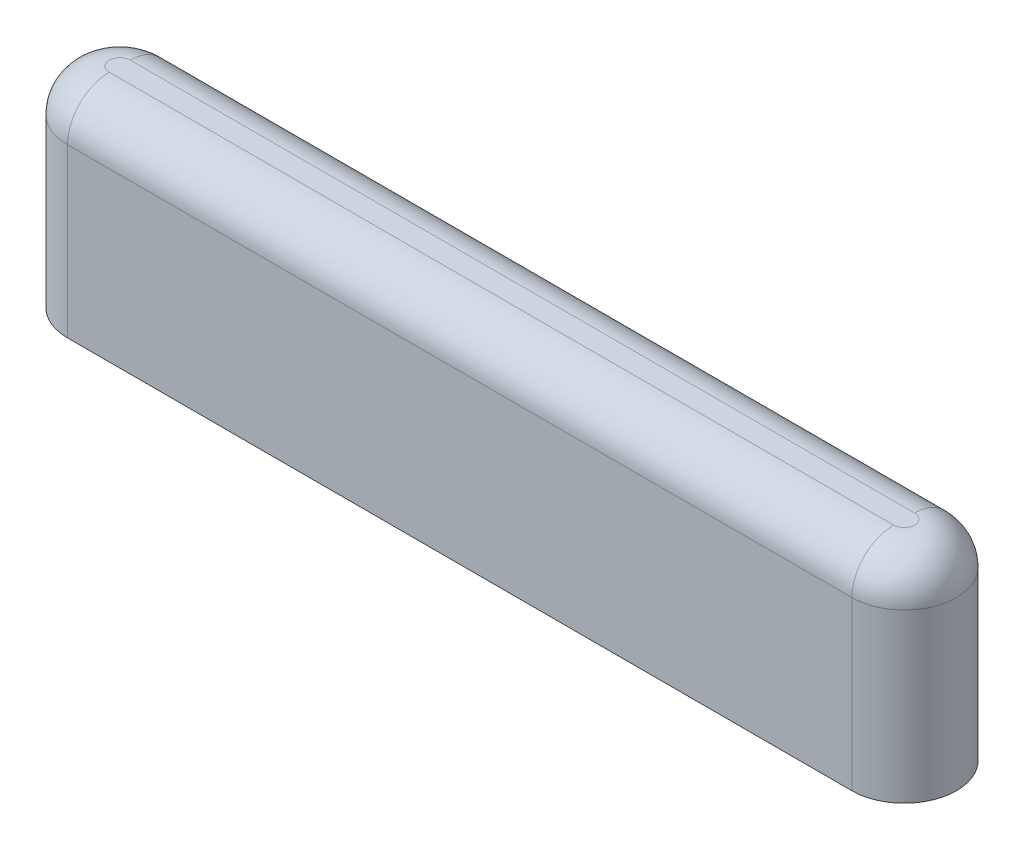
SolidWorks part; units mm, degrees
material "1060 Alloy"
ref_plane "Front Plane" through (0, 0, 0) normal (0, 0, 1) x (1, 0, 0)
ref_plane "Top Plane" through (0, 0, 0) normal (0, 1, 0) x (1, 0, 0)
ref_plane "Right Plane" through (0, 0, 0) normal (1, 0, 0) x (0, 0, -1)
sketch "Sketch1" plane through (0, 0, 0) normal (0, 1, 0) x (1, 0, 0)
  line L1 (37.5, -5) -> (-37.5, -5)
  line L2 (37.5, -5) -> (37.5, 5) construction
  line L3 (37.5, 5) -> (-37.5, 5)
  line L4 (-37.5, -5) -> (-37.5, 5) construction
  line L5 (37.5, -5) -> (-37.5, 5) construction
  line L6 (37.5, 5) -> (-37.5, -5) construction
  arc A0 (-37.5, -5) -> (-37.5, 5) centre (-37.5, 0) cw
  arc A1 (37.5, -5) -> (37.5, 5) centre (37.5, 0) ccw
  point P0 (0, 0)
  dimension "D1" = 75
  dimension "D2" = 10
extrude "Boss-Extrude1" add sketch "Sketch1" along normal blind 20 contours L1 A0 L3 A1
fillet "Fillet1" radius 4 4 edges at (42.5, 20, 0) (0, 20, -5) (-42.5, 20, 0) (0, 20, 5)
sketch "Sketch2" plane through (0, 0, 0) normal (0, -1, 0) x (1, 0, 0)
  circle A0 centre (-37.5, 0) radius 2.75
  dimension "D1" = 5.5
extrude "Cut-Extrude1" cut sketch "Sketch2" against normal blind 1.5
pattern_linear "LPattern1" count 3 spacing 30 along (1, 0, 0) of "Cut-Extrude1"
